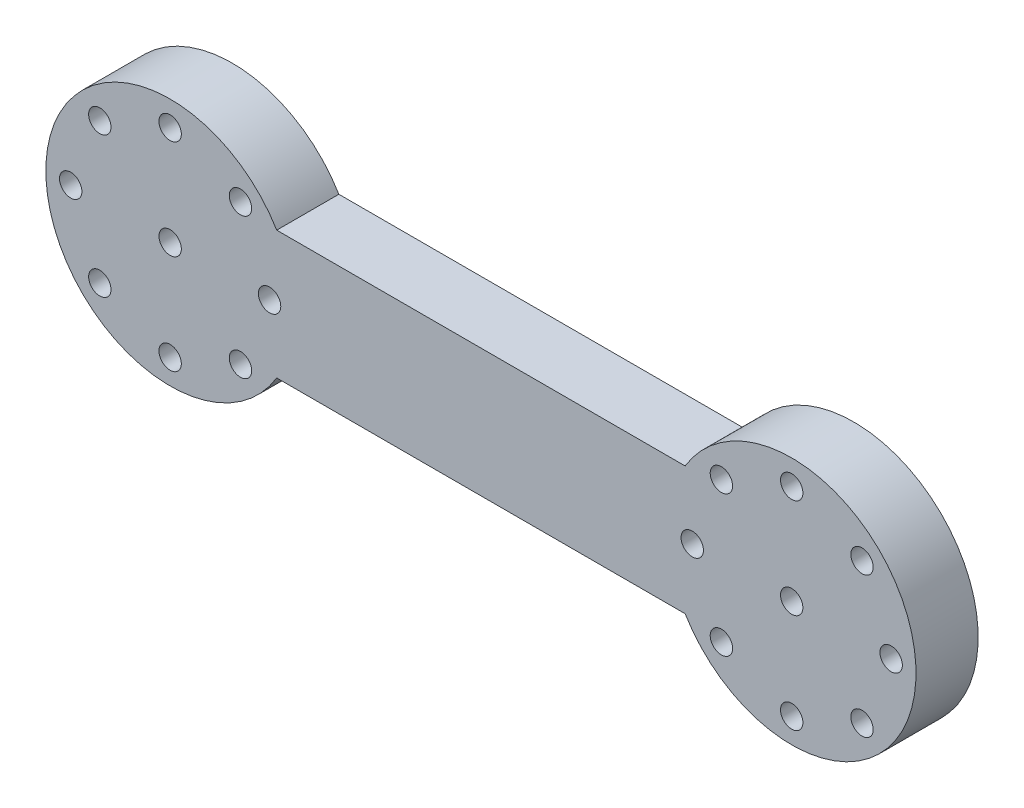
SolidWorks part; units mm, degrees
ref_plane "Plan de face" through (0, 0, 0) normal (0, 0, 1) x (1, 0, 0)
ref_plane "Plan de dessus" through (0, 0, 0) normal (0, 1, 0) x (1, 0, 0)
ref_plane "Plan de droite" through (0, 0, 0) normal (1, 0, 0) x (0, 0, -1)
sketch "Esquisse1" plane through (0, 0, 0) normal (0, 0, 1) x (1, 0, 0)
  line L0 (0, 0) -> (50, 0) construction
  line L1 (0, 5.1477) -> (50, 5.1477)
  line L2 (0, -5.1477) -> (50, -5.1477)
  arc A0 (0, 5.1477) -> (0, -5.1477) centre (0, 0) ccw
  arc A1 (50, -5.1477) -> (50, 5.1477) centre (50, 0) ccw
  circle A2 centre (0, 0) radius 2.45
  circle A3 centre (50, 0) radius 2.45
  point P3 (25, 0)
  dimension "D1" = 50
extrude "Boss.-Extru.1" add sketch "Esquisse1" along normal blind 5
sketch "Esquisse2" plane through (0, 0, 5) normal (0, 0, 1) x (1, 0, 0)
  line L0 (25, 5.1477) -> (25, -5.1477) construction
  line L1 (50, 5.1477) -> (0, 5.1477) construction
  line L2 (0, -5.1477) -> (50, -5.1477) construction
  circle A0 centre (0, 0) radius 2.45
  circle A1 centre (0, 0) radius 0.9
  circle A2 centre (50, 0) radius 0.9
  circle A3 centre (50, 0) radius 2.45
extrude "Boss.-Extru.2" add sketch "Esquisse2" against normal blind 2.53
sketch "Esquisse4" plane through (0, 0, 5) normal (0, 0, 1) x (1, 0, 0)
  circle A0 centre (0, 0) radius 10
  circle A1 centre (0, 0) radius 2.45
  circle A2 centre (50, 0) radius 2.45
  circle A3 centre (50, 0) radius 10
extrude "Boss.-Extru.4" add sketch "Esquisse4" against normal blind 5
sketch "Esquisse5" plane through (0, 0, 5) normal (0, 0, 1) x (1, 0, 0)
  line L0 (0, 0) -> (-10, 0) construction
  line L1 (25, 5.1477) -> (25, -5.1477) construction
  line L2 (41.4267, 5.1477) -> (8.5733, 5.1477) construction
  line L3 (8.5733, -5.1477) -> (41.4267, -5.1477) construction
  arc A0 (8.5733, 5.1477) -> (8.5733, -5.1477) centre (0, 0) ccw construction
  circle A1 centre (0, 0) radius 8 construction
  circle A2 centre (-8, 0) radius 0.9
  circle A3 centre (-5.6569, 5.6569) radius 0.9
  circle A4 centre (0, 8) radius 0.9
  circle A5 centre (5.6569, 5.6569) radius 0.9
  circle A6 centre (8, 0) radius 0.9
  circle A7 centre (5.6569, -5.6569) radius 0.9
  circle A8 centre (0, -8) radius 0.9
  circle A9 centre (-5.6569, -5.6569) radius 0.9
  circle A10 centre (44.3431, 5.6569) radius 0.9
  circle A11 centre (42, 0) radius 0.9
  circle A12 centre (44.3431, -5.6569) radius 0.9
  circle A13 centre (50, -8) radius 0.9
  circle A14 centre (55.6569, -5.6569) radius 0.9
  circle A15 centre (58, 0) radius 0.9
  circle A16 centre (55.6569, 5.6569) radius 0.9
  circle A17 centre (50, 8) radius 0.9
  point P25 (0, 0)
  dimension "D1" = 8
extrude "Enlèv. mat.-Extru.3" cut sketch "Esquisse5" against normal blind 10
ref_plane "Plan1" through (8.5733, 5.1477, 5) normal (-0.5148, 0.8573, 0) x (0, 0, 1)
